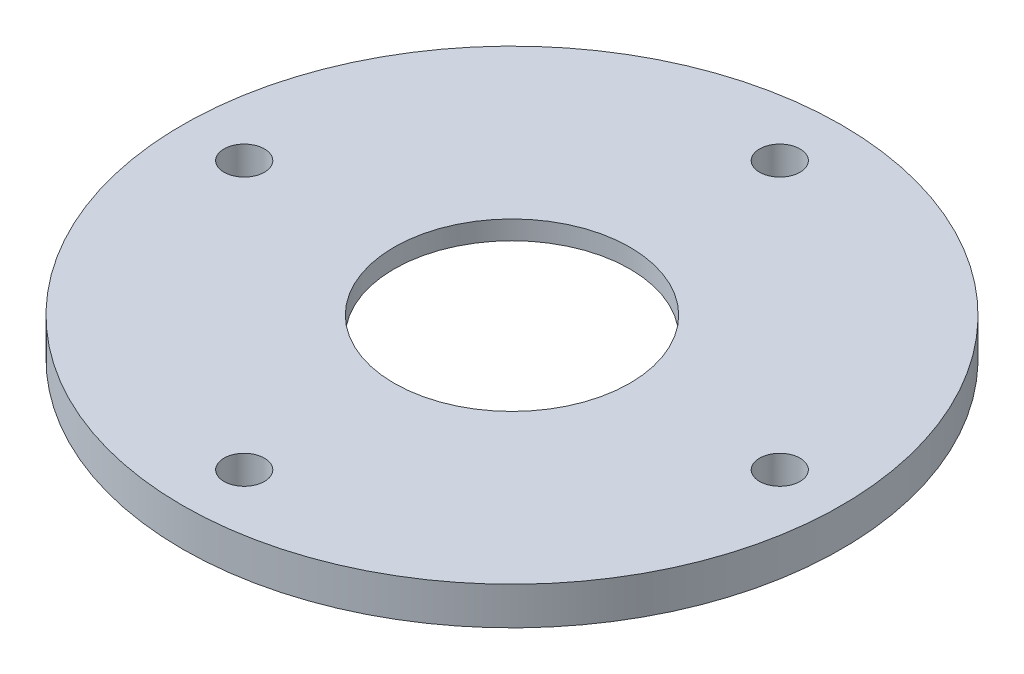
SolidWorks part; units mm, degrees
ref_plane "Front Plane" through (0, 0, 0) normal (0, 0, 1) x (1, 0, 0)
ref_plane "Top Plane" through (0, 0, 0) normal (0, 1, 0) x (1, 0, 0)
ref_plane "Right Plane" through (0, 0, 0) normal (1, 0, 0) x (0, 0, -1)
sketch "Sketch1" plane through (0, 0, 0) normal (0, 0, 1) x (1, 0, 0)
  line L0 (12.3063, 0) -> (12.3063, 1.5875)
  line L1 (12.3063, 1.5875) -> (9.906, 1.5875)
  line L2 (9.906, 1.5875) -> (9.906, 3.175)
  line L3 (9.906, 3.175) -> (27.69, 3.175)
  line L4 (27.69, 3.175) -> (27.69, 0)
  line L5 (27.69, 0) -> (12.3063, 0)
  line L6 (0, 0) -> (0, 23.5305) construction
  dimension "D1" = 12.3063
  dimension "D2" = 27.69
  dimension "D3" = 3.175
  dimension "D4" = 1.5875
  dimension "D5" = 9.906
revolve "Revolve1" add sketch "Sketch1" angle 360 about L6
sketch "Sketch2" plane through (0, 3.175, 0) normal (0, 1, 0) x (1, 0, 0)
  circle A0 centre (0, 0) radius 22.5 construction
  point P3 (0, 22.5)
  point P4 (-22.5, 0)
  point P5 (0, -22.5)
  point P6 (22.5, 0)
  dimension "D1" = 45
hole_wizard "M3 Clearance Hole1" positions "Sketch2" profile "Sketch3" hole size "M3" standard "ANSI Metric" end condition up to next
sketch "Sketch3" plane through (22.5, 3.175, 0) normal (1, 0, 0) x (0, 0, 1)
  line L0 (0, 0) -> (0, 3.175)
  line L1 (0, 3.175) -> (1.7, 3.175)
  line L2 (1.7, 3.175) -> (1.7, 0)
  line L5 (1.7, 0) -> (0, 0)
  line L11 (0, -6.35) -> (0, 107.95) construction
  dimension "Thru Hole Dia." = 3.4
  dimension "Thru Hole Depth" = 3.175
